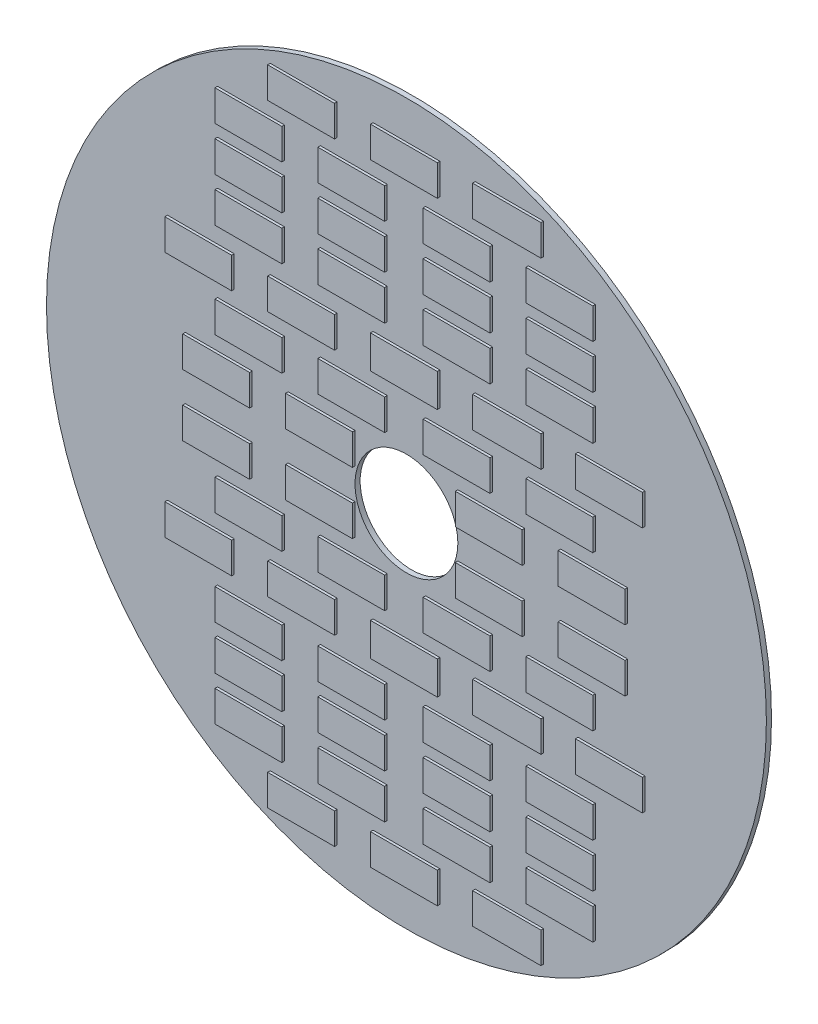
SolidWorks part; units mm, degrees
ref_plane "前视基准面" through (0, 0, 0) normal (0, 0, 1) x (1, 0, 0)
ref_plane "上视基准面" through (0, 0, 0) normal (0, 1, 0) x (1, 0, 0)
ref_plane "右视基准面" through (0, 0, 0) normal (1, 0, 0) x (0, 0, -1)
other "Configuration Table"
sketch "草图1" plane through (0, 0, 0) normal (0, 0, 1) x (1, 0, 0)
  line L5 (100, 90) -> (230, 90)
  line L6 (100, 90) -> (100, 30)
  line L8 (100, 30) -> (230, 30)
  line L12 (230, 90) -> (230, 30)
  line L14 (100, 90) -> (230, 30) construction
  line L18 (100, 30) -> (230, 90) construction
  line L24 (-1658.199, 0) -> (1658.199, 0) construction
  line L26 (0, 1113.9389) -> (0, -1113.9389) construction
  line L50 (300, 90) -> (430, 90)
  line L53 (300, 90) -> (300, 30)
  line L57 (300, 30) -> (430, 30)
  line L58 (430, 90) -> (430, 30)
  line L59 (300, 90) -> (430, 30) construction
  line L60 (300, 30) -> (430, 90) construction
  line L61 (37.3566, 180) -> (37.3566, 120)
  line L62 (237.3566, 120) -> (367.3566, 120)
  line L63 (237.3566, 180) -> (367.3566, 120) construction
  line L64 (37.3566, 120) -> (167.3566, 180) construction
  line L65 (237.3566, 180) -> (237.3566, 120)
  line L66 (367.3566, 180) -> (367.3566, 120)
  line L67 (37.3566, 180) -> (167.3566, 180)
  line L68 (37.3566, 180) -> (167.3566, 120) construction
  line L69 (237.3566, 180) -> (367.3566, 180)
  line L70 (237.3566, 120) -> (367.3566, 180) construction
  line L71 (37.3566, 120) -> (167.3566, 120)
  line L72 (167.3566, 180) -> (167.3566, 120)
  line L83 (37.3566, 364.2375) -> (37.3566, 304.2375)
  line L84 (237.3566, 304.2375) -> (367.3566, 304.2375)
  line L91 (133.7252, 270) -> (133.7252, 210)
  line L92 (333.7252, 210) -> (463.7252, 210)
  line L93 (333.7252, 270) -> (463.7252, 210) construction
  line L94 (133.7252, 210) -> (266.6142, 270) construction
  line L95 (333.7252, 270) -> (333.7252, 210)
  line L96 (463.7252, 270) -> (463.7252, 210)
  line L97 (133.7252, 270) -> (266.6142, 270)
  line L98 (133.7252, 270) -> (266.6142, 210) construction
  line L99 (333.7252, 270) -> (463.7252, 270)
  line L100 (333.7252, 210) -> (463.7252, 270) construction
  line L101 (133.7252, 210) -> (266.6142, 210)
  line L102 (266.6142, 270) -> (266.6142, 210)
  line L103 (-65, 274.2375) -> (-65, 210)
  line L104 (-65, 274.2375) -> (65, 274.2375)
  line L105 (-65, 210) -> (65, 210)
  line L106 (65, 274.2375) -> (65, 210)
  line L107 (-65, 210) -> (65, 274.2375) construction
  line L108 (-65, 274.2375) -> (65, 210) construction
  line L109 (-264.8303, 270) -> (-264.8303, 210)
  line L110 (-264.8303, 270) -> (-134.8303, 270)
  line L111 (-264.8303, 210) -> (-134.8303, 210)
  line L112 (-134.8303, 270) -> (-134.8303, 210)
  line L113 (-264.8303, 210) -> (-134.8303, 270) construction
  line L114 (-264.8303, 270) -> (-134.8303, 210) construction
  line L115 (-464.8303, 270) -> (-464.8303, 210)
  line L116 (-464.8303, 270) -> (-334.8303, 270)
  line L117 (-464.8303, 210) -> (-334.8303, 210)
  line L118 (-334.8303, 270) -> (-334.8303, 210)
  line L119 (-464.8303, 210) -> (-334.8303, 270) construction
  line L120 (-464.8303, 270) -> (-334.8303, 210) construction
  line L122 (237.3566, 364.2375) -> (237.3566, 304.2375)
  line L123 (367.3566, 364.2375) -> (367.3566, 304.2375)
  line L125 (37.3566, 364.2375) -> (167.3566, 364.2375)
  line L127 (237.3566, 364.2375) -> (367.3566, 364.2375)
  line L128 (37.3566, 304.2375) -> (167.3566, 304.2375)
  line L129 (167.3566, 364.2375) -> (167.3566, 304.2375)
  line L139 (237.3566, 364.2375) -> (367.3566, 304.2375) construction
  line L140 (37.3566, 304.2375) -> (167.3566, 364.2375) construction
  line L141 (37.3566, 364.2375) -> (167.3566, 304.2375) construction
  line L142 (237.3566, 304.2375) -> (367.3566, 364.2375) construction
  line L143 (37.3566, 450) -> (37.3566, 390)
  line L144 (237.3566, 390) -> (367.3566, 390)
  line L145 (237.3566, 450) -> (237.3566, 390)
  line L146 (367.3566, 450) -> (367.3566, 390)
  line L147 (37.3566, 450) -> (167.3566, 450)
  line L148 (237.3566, 450) -> (367.3566, 450)
  line L149 (37.3566, 390) -> (167.3566, 390)
  line L150 (167.3566, 450) -> (167.3566, 390)
  line L151 (237.3566, 450) -> (367.3566, 390) construction
  line L152 (37.3566, 390) -> (167.3566, 450) construction
  line L153 (37.3566, 450) -> (167.3566, 390) construction
  line L154 (237.3566, 390) -> (367.3566, 450) construction
  line L155 (37.3566, 535.7625) -> (37.3566, 475.7625)
  line L156 (237.3566, 475.7625) -> (367.3566, 475.7625)
  line L157 (237.3566, 535.7625) -> (237.3566, 475.7625)
  line L158 (367.3566, 535.7625) -> (367.3566, 475.7625)
  line L159 (37.3566, 535.7625) -> (167.3566, 535.7625)
  line L160 (237.3566, 535.7625) -> (367.3566, 535.7625)
  line L161 (37.3566, 475.7625) -> (167.3566, 475.7625)
  line L162 (167.3566, 535.7625) -> (167.3566, 475.7625)
  line L163 (237.3566, 535.7625) -> (367.3566, 475.7625) construction
  line L164 (37.3566, 475.7625) -> (167.3566, 535.7625) construction
  line L165 (37.3566, 535.7625) -> (167.3566, 475.7625) construction
  line L166 (237.3566, 475.7625) -> (367.3566, 535.7625) construction
  line L167 (-264.8303, 565.7625) -> (-134.8303, 625.7625) construction
  line L168 (133.7252, 565.7625) -> (266.6142, 565.7625)
  line L169 (-65, 565.7625) -> (65, 625.7625) construction
  line L170 (-65, 625.7625) -> (-65, 565.7625)
  line L171 (-264.8303, 625.7625) -> (-264.8303, 565.7625)
  line L172 (-134.8303, 625.7625) -> (-134.8303, 565.7625)
  line L173 (133.7252, 625.7625) -> (266.6142, 625.7625)
  line L174 (133.7252, 625.7625) -> (266.6142, 565.7625) construction
  line L175 (65, 625.7625) -> (65, 565.7625)
  line L176 (-264.8303, 625.7625) -> (-134.8303, 565.7625) construction
  line L177 (133.7252, 625.7625) -> (133.7252, 565.7625)
  line L178 (-65, 625.7625) -> (65, 625.7625)
  line L179 (-65, 565.7625) -> (65, 565.7625)
  line L180 (-264.8303, 565.7625) -> (-134.8303, 565.7625)
  line L181 (133.7252, 565.7625) -> (266.6142, 625.7625) construction
  line L182 (266.6142, 625.7625) -> (266.6142, 565.7625)
  line L183 (-264.8303, 625.7625) -> (-134.8303, 625.7625)
  line L184 (-65, 625.7625) -> (65, 565.7625) construction
  line L185 (-300, 90) -> (-300, 30)
  line L186 (-300, 30) -> (-430, 30)
  line L187 (-430, 90) -> (-430, 30)
  line L188 (-300, 90) -> (-430, 90)
  line L189 (-100, 30) -> (-230, 30)
  line L190 (-230, 90) -> (-230, 30)
  line L191 (-100, 90) -> (-230, 90)
  line L192 (-100, 90) -> (-100, 30)
  line L193 (-37.3566, 180) -> (-167.3566, 180)
  line L194 (-167.3566, 180) -> (-167.3566, 120)
  line L195 (-37.3566, 120) -> (-167.3566, 120)
  line L196 (-37.3566, 180) -> (-37.3566, 120)
  line L197 (-237.3566, 180) -> (-237.3566, 120)
  line L198 (-237.3566, 180) -> (-367.3566, 180)
  line L199 (-367.3566, 180) -> (-367.3566, 120)
  line L200 (-237.3566, 120) -> (-367.3566, 120)
  line L201 (-237.3566, 475.7625) -> (-367.3566, 535.7625) construction
  line L202 (-37.3566, 535.7625) -> (-167.3566, 475.7625) construction
  line L203 (-37.3566, 475.7625) -> (-167.3566, 535.7625) construction
  line L204 (-237.3566, 535.7625) -> (-367.3566, 475.7625) construction
  line L205 (-237.3566, 390) -> (-367.3566, 450) construction
  line L206 (-37.3566, 450) -> (-167.3566, 390) construction
  line L207 (-37.3566, 390) -> (-167.3566, 450) construction
  line L208 (-237.3566, 450) -> (-367.3566, 390) construction
  line L209 (-237.3566, 304.2375) -> (-367.3566, 364.2375) construction
  line L210 (-37.3566, 364.2375) -> (-167.3566, 304.2375) construction
  line L211 (-37.3566, 304.2375) -> (-167.3566, 364.2375) construction
  line L212 (-237.3566, 364.2375) -> (-367.3566, 304.2375) construction
  line L213 (-167.3566, 535.7625) -> (-167.3566, 475.7625)
  line L214 (-37.3566, 475.7625) -> (-167.3566, 475.7625)
  line L215 (-237.3566, 535.7625) -> (-367.3566, 535.7625)
  line L216 (-37.3566, 535.7625) -> (-167.3566, 535.7625)
  line L217 (-367.3566, 535.7625) -> (-367.3566, 475.7625)
  line L218 (-237.3566, 535.7625) -> (-237.3566, 475.7625)
  line L219 (-237.3566, 475.7625) -> (-367.3566, 475.7625)
  line L220 (-37.3566, 535.7625) -> (-37.3566, 475.7625)
  line L221 (-167.3566, 450) -> (-167.3566, 390)
  line L222 (-37.3566, 390) -> (-167.3566, 390)
  line L223 (-237.3566, 450) -> (-367.3566, 450)
  line L224 (-37.3566, 450) -> (-167.3566, 450)
  line L225 (-367.3566, 450) -> (-367.3566, 390)
  line L226 (-237.3566, 450) -> (-237.3566, 390)
  line L227 (-237.3566, 390) -> (-367.3566, 390)
  line L228 (-37.3566, 450) -> (-37.3566, 390)
  line L229 (-167.3566, 364.2375) -> (-167.3566, 304.2375)
  line L230 (-37.3566, 304.2375) -> (-167.3566, 304.2375)
  line L231 (-237.3566, 364.2375) -> (-367.3566, 364.2375)
  line L232 (-37.3566, 364.2375) -> (-167.3566, 364.2375)
  line L233 (-367.3566, 364.2375) -> (-367.3566, 304.2375)
  line L234 (-237.3566, 364.2375) -> (-237.3566, 304.2375)
  line L235 (-237.3566, 304.2375) -> (-367.3566, 304.2375)
  line L236 (-37.3566, 364.2375) -> (-37.3566, 304.2375)
  line L237 (-237.3566, -364.2375) -> (-367.3566, -304.2375) construction
  line L238 (-37.3566, -304.2375) -> (-167.3566, -364.2375) construction
  line L239 (-37.3566, -364.2375) -> (-167.3566, -304.2375) construction
  line L240 (-237.3566, -304.2375) -> (-367.3566, -364.2375) construction
  line L241 (-237.3566, -450) -> (-367.3566, -390) construction
  line L242 (-37.3566, -390) -> (-167.3566, -450) construction
  line L243 (-37.3566, -450) -> (-167.3566, -390) construction
  line L244 (-237.3566, -390) -> (-367.3566, -450) construction
  line L245 (-237.3566, -535.7625) -> (-367.3566, -475.7625) construction
  line L246 (-37.3566, -475.7625) -> (-167.3566, -535.7625) construction
  line L247 (-37.3566, -535.7625) -> (-167.3566, -475.7625) construction
  line L248 (-237.3566, -475.7625) -> (-367.3566, -535.7625) construction
  line L249 (-65, -625.7625) -> (65, -565.7625) construction
  line L250 (133.7252, -565.7625) -> (266.6142, -625.7625) construction
  line L251 (-264.8303, -625.7625) -> (-134.8303, -565.7625) construction
  line L252 (133.7252, -625.7625) -> (266.6142, -565.7625) construction
  line L253 (-65, -565.7625) -> (65, -625.7625) construction
  line L254 (-264.8303, -565.7625) -> (-134.8303, -625.7625) construction
  line L255 (237.3566, -475.7625) -> (367.3566, -535.7625) construction
  line L256 (37.3566, -535.7625) -> (167.3566, -475.7625) construction
  line L257 (37.3566, -475.7625) -> (167.3566, -535.7625) construction
  line L258 (237.3566, -535.7625) -> (367.3566, -475.7625) construction
  line L259 (237.3566, -390) -> (367.3566, -450) construction
  line L260 (37.3566, -450) -> (167.3566, -390) construction
  line L261 (37.3566, -390) -> (167.3566, -450) construction
  line L262 (237.3566, -450) -> (367.3566, -390) construction
  line L263 (237.3566, -304.2375) -> (367.3566, -364.2375) construction
  line L264 (37.3566, -364.2375) -> (167.3566, -304.2375) construction
  line L265 (37.3566, -304.2375) -> (167.3566, -364.2375) construction
  line L266 (237.3566, -364.2375) -> (367.3566, -304.2375) construction
  line L267 (-464.8303, -270) -> (-334.8303, -210) construction
  line L268 (-464.8303, -210) -> (-334.8303, -270) construction
  line L269 (-264.8303, -270) -> (-134.8303, -210) construction
  line L270 (-264.8303, -210) -> (-134.8303, -270) construction
  line L271 (-65, -274.2375) -> (65, -210) construction
  line L272 (-65, -210) -> (65, -274.2375) construction
  line L273 (333.7252, -210) -> (463.7252, -270) construction
  line L274 (133.7252, -270) -> (266.6142, -210) construction
  line L275 (133.7252, -210) -> (266.6142, -270) construction
  line L276 (333.7252, -270) -> (463.7252, -210) construction
  line L277 (237.3566, -120) -> (367.3566, -180) construction
  line L278 (37.3566, -180) -> (167.3566, -120) construction
  line L279 (37.3566, -120) -> (167.3566, -180) construction
  line L280 (237.3566, -180) -> (367.3566, -120) construction
  line L281 (300, -30) -> (430, -90) construction
  line L282 (300, -90) -> (430, -30) construction
  line L283 (100, -30) -> (230, -90) construction
  line L284 (100, -90) -> (230, -30) construction
  line L285 (-37.3566, -364.2375) -> (-37.3566, -304.2375)
  line L286 (-237.3566, -304.2375) -> (-367.3566, -304.2375)
  line L287 (-237.3566, -364.2375) -> (-237.3566, -304.2375)
  line L288 (-367.3566, -364.2375) -> (-367.3566, -304.2375)
  line L289 (-37.3566, -364.2375) -> (-167.3566, -364.2375)
  line L290 (-237.3566, -364.2375) -> (-367.3566, -364.2375)
  line L291 (-37.3566, -304.2375) -> (-167.3566, -304.2375)
  line L292 (-167.3566, -364.2375) -> (-167.3566, -304.2375)
  line L293 (-37.3566, -450) -> (-37.3566, -390)
  line L294 (-237.3566, -390) -> (-367.3566, -390)
  line L295 (-237.3566, -450) -> (-237.3566, -390)
  line L296 (-367.3566, -450) -> (-367.3566, -390)
  line L297 (-37.3566, -450) -> (-167.3566, -450)
  line L298 (-237.3566, -450) -> (-367.3566, -450)
  line L299 (-37.3566, -390) -> (-167.3566, -390)
  line L300 (-167.3566, -450) -> (-167.3566, -390)
  line L301 (-37.3566, -535.7625) -> (-37.3566, -475.7625)
  line L302 (-237.3566, -475.7625) -> (-367.3566, -475.7625)
  line L303 (-237.3566, -535.7625) -> (-237.3566, -475.7625)
  line L304 (-367.3566, -535.7625) -> (-367.3566, -475.7625)
  line L305 (-37.3566, -535.7625) -> (-167.3566, -535.7625)
  line L306 (-237.3566, -535.7625) -> (-367.3566, -535.7625)
  line L307 (-37.3566, -475.7625) -> (-167.3566, -475.7625)
  line L308 (-167.3566, -535.7625) -> (-167.3566, -475.7625)
  line L309 (-237.3566, -120) -> (-367.3566, -120)
  line L310 (-367.3566, -180) -> (-367.3566, -120)
  line L311 (-237.3566, -180) -> (-367.3566, -180)
  line L312 (-237.3566, -180) -> (-237.3566, -120)
  line L313 (-37.3566, -180) -> (-37.3566, -120)
  line L314 (-37.3566, -120) -> (-167.3566, -120)
  line L315 (-167.3566, -180) -> (-167.3566, -120)
  line L316 (-37.3566, -180) -> (-167.3566, -180)
  line L317 (-100, -90) -> (-100, -30)
  line L318 (-100, -90) -> (-230, -90)
  line L319 (-230, -90) -> (-230, -30)
  line L320 (-100, -30) -> (-230, -30)
  line L321 (-300, -90) -> (-430, -90)
  line L322 (-430, -90) -> (-430, -30)
  line L323 (-300, -30) -> (-430, -30)
  line L324 (-300, -90) -> (-300, -30)
  line L325 (-264.8303, -625.7625) -> (-134.8303, -625.7625)
  line L326 (266.6142, -625.7625) -> (266.6142, -565.7625)
  line L327 (-264.8303, -565.7625) -> (-134.8303, -565.7625)
  line L328 (-65, -565.7625) -> (65, -565.7625)
  line L329 (-65, -625.7625) -> (65, -625.7625)
  line L330 (133.7252, -625.7625) -> (133.7252, -565.7625)
  line L331 (65, -625.7625) -> (65, -565.7625)
  line L332 (133.7252, -625.7625) -> (266.6142, -625.7625)
  line L333 (-134.8303, -625.7625) -> (-134.8303, -565.7625)
  line L334 (-264.8303, -625.7625) -> (-264.8303, -565.7625)
  line L335 (-65, -625.7625) -> (-65, -565.7625)
  line L336 (133.7252, -565.7625) -> (266.6142, -565.7625)
  line L337 (167.3566, -535.7625) -> (167.3566, -475.7625)
  line L338 (37.3566, -475.7625) -> (167.3566, -475.7625)
  line L339 (237.3566, -535.7625) -> (367.3566, -535.7625)
  line L340 (37.3566, -535.7625) -> (167.3566, -535.7625)
  line L341 (367.3566, -535.7625) -> (367.3566, -475.7625)
  line L342 (237.3566, -535.7625) -> (237.3566, -475.7625)
  line L343 (237.3566, -475.7625) -> (367.3566, -475.7625)
  line L344 (37.3566, -535.7625) -> (37.3566, -475.7625)
  line L345 (167.3566, -450) -> (167.3566, -390)
  line L346 (37.3566, -390) -> (167.3566, -390)
  line L347 (237.3566, -450) -> (367.3566, -450)
  line L348 (37.3566, -450) -> (167.3566, -450)
  line L349 (367.3566, -450) -> (367.3566, -390)
  line L350 (237.3566, -450) -> (237.3566, -390)
  line L351 (237.3566, -390) -> (367.3566, -390)
  line L352 (37.3566, -450) -> (37.3566, -390)
  line L353 (167.3566, -364.2375) -> (167.3566, -304.2375)
  line L354 (37.3566, -304.2375) -> (167.3566, -304.2375)
  line L355 (237.3566, -364.2375) -> (367.3566, -364.2375)
  line L356 (37.3566, -364.2375) -> (167.3566, -364.2375)
  line L357 (367.3566, -364.2375) -> (367.3566, -304.2375)
  line L358 (237.3566, -364.2375) -> (237.3566, -304.2375)
  line L359 (-334.8303, -270) -> (-334.8303, -210)
  line L360 (-464.8303, -210) -> (-334.8303, -210)
  line L361 (-464.8303, -270) -> (-334.8303, -270)
  line L362 (-464.8303, -270) -> (-464.8303, -210)
  line L363 (-134.8303, -270) -> (-134.8303, -210)
  line L364 (-264.8303, -210) -> (-134.8303, -210)
  line L365 (-264.8303, -270) -> (-134.8303, -270)
  line L366 (-264.8303, -270) -> (-264.8303, -210)
  line L367 (65, -274.2375) -> (65, -210)
  line L368 (-65, -210) -> (65, -210)
  line L369 (-65, -274.2375) -> (65, -274.2375)
  line L370 (-65, -274.2375) -> (-65, -210)
  line L371 (266.6142, -270) -> (266.6142, -210)
  line L372 (133.7252, -210) -> (266.6142, -210)
  line L373 (333.7252, -270) -> (463.7252, -270)
  line L374 (133.7252, -270) -> (266.6142, -270)
  line L375 (463.7252, -270) -> (463.7252, -210)
  line L376 (333.7252, -270) -> (333.7252, -210)
  line L377 (333.7252, -210) -> (463.7252, -210)
  line L378 (133.7252, -270) -> (133.7252, -210)
  line L379 (237.3566, -304.2375) -> (367.3566, -304.2375)
  line L380 (37.3566, -364.2375) -> (37.3566, -304.2375)
  line L381 (167.3566, -180) -> (167.3566, -120)
  line L382 (37.3566, -120) -> (167.3566, -120)
  line L383 (237.3566, -180) -> (367.3566, -180)
  line L384 (37.3566, -180) -> (167.3566, -180)
  line L385 (367.3566, -180) -> (367.3566, -120)
  line L386 (237.3566, -180) -> (237.3566, -120)
  line L387 (237.3566, -120) -> (367.3566, -120)
  line L388 (37.3566, -180) -> (37.3566, -120)
  line L389 (430, -90) -> (430, -30)
  line L390 (300, -30) -> (430, -30)
  line L391 (300, -90) -> (300, -30)
  line L392 (300, -90) -> (430, -90)
  line L393 (230, -90) -> (230, -30)
  line L394 (100, -30) -> (230, -30)
  line L395 (100, -90) -> (100, -30)
  line L396 (100, -90) -> (230, -90)
  circle A0 centre (0, 0) radius 700 construction
  point P0 (165, 60)
  point P5 (102.3566, 150)
  point P7 (365, 60)
  point P16 (302.3566, 192.8005)
  point P24 (200.1697, 595.7625)
  point P26 (200.1697, 240)
  point P29 (102.3566, 334.2375)
  point P39 (102.3566, 420)
  point P47 (0, 274.2375)
  point P70 (102.3566, 505.7625)
  point P80 (302.3566, 462.8005)
  point P81 (302.3566, 377.038)
  point P132 (-102.3566, 505.7625)
  point P133 (-102.3566, 420)
  point P134 (-102.3566, 334.2375)
  point P247 (-102.3566, -334.2375)
  point P248 (-102.3566, -420)
  point P249 (-102.3566, -505.7625)
  point P250 (102.3566, -505.7625)
  point P251 (102.3566, -420)
  point P252 (102.3566, -334.2375)
  point P253 (200.1697, -240)
  point P254 (200.1697, -595.7625)
  point P255 (302.3566, -192.8005)
  point P256 (365, -60)
  point P257 (102.3566, -150)
  point P258 (165, -60)
  dimension "D3" = 100
  dimension "D1" = 2
  dimension "D2" = 30
  dimension "D4" = 30
  dimension "D5" = 60
  dimension "D6" = 130
  dimension "D7" = 70
  dimension "D8" = 70
  dimension "D9" = 2
  dimension "D10" = 3
  dimension "D11" = 130
  dimension "D12" = 60
  dimension "D13" = 30
  dimension "D14" = 60
  dimension "D15" = 30
sketch "草图2" plane through (0, 0, 0) normal (0, 0, 1) x (1, 0, 0)
  circle A0 centre (0, 0) radius 700
  circle A1 centre (0, 0) radius 100
extrude "凸台-拉伸1" add sketch "草图2" along normal blind 10
extrude "凸台-拉伸2" add sketch "草图1" along normal blind 15
